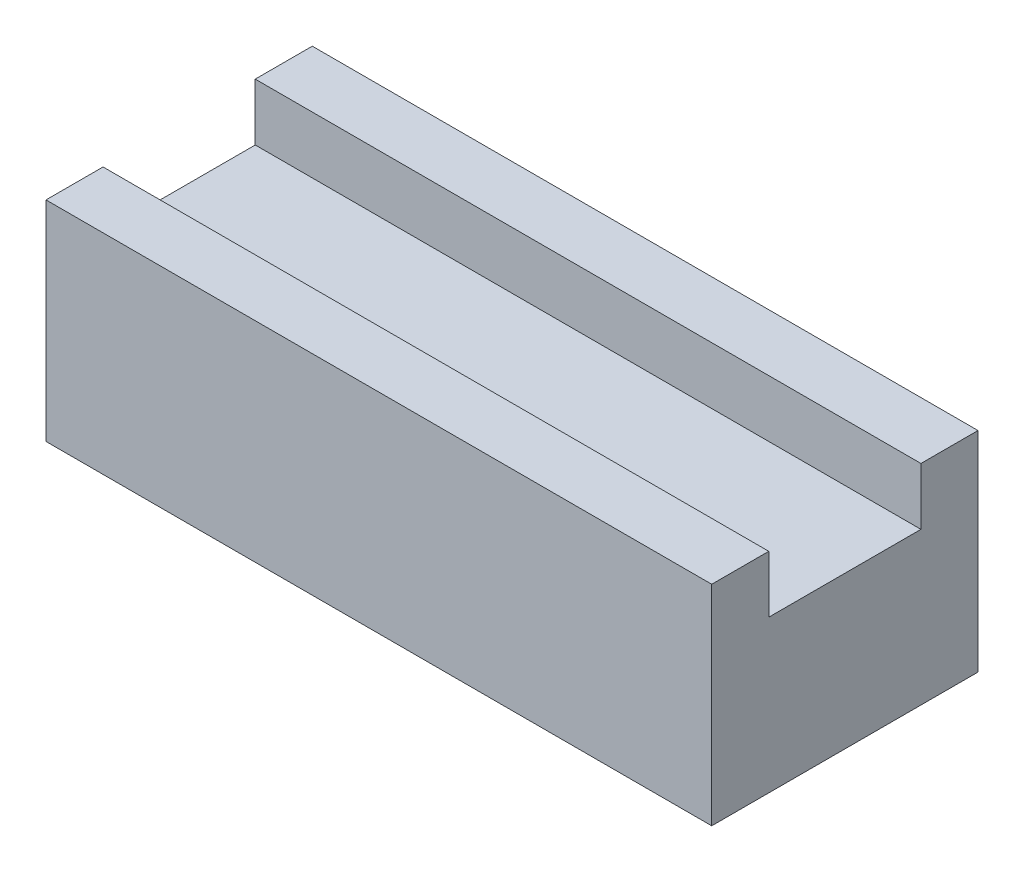
SolidWorks part; units mm, degrees
ref_plane "Front Plane" through (0, 0, 0) normal (0, 0, 1) x (1, 0, 0)
ref_plane "Top Plane" through (0, 0, 0) normal (0, 1, 0) x (1, 0, 0)
ref_plane "Right Plane" through (0, 0, 0) normal (1, 0, 0) x (0, 0, -1)
sketch "Sketch1" plane through (0, 0, 0) normal (1, 0, 0) x (0, 0, -1)
  line L0 (-7, 4) -> (-7, 7)
  line L1 (-7, -4) -> (7, -4)
  line L2 (-7, -4) -> (-7, 4)
  line L3 (-4, 4) -> (4, 4)
  line L4 (7, -4) -> (7, 4)
  line L5 (-7, -4) -> (7, 4) construction
  line L6 (-7, 4) -> (7, -4) construction
  line L7 (-7, 7) -> (-4, 7)
  line L8 (-4, 7) -> (-4, 4)
  line L9 (7, 4) -> (7, 7)
  line L10 (7, 7) -> (4, 7)
  line L11 (4, 7) -> (4, 4)
  point P0 (0, 0)
  point P12 (0, 4)
  point P13 (-4, 1.3048)
  point P14 (0, 0)
  point P15 (-7, 2.3631)
  dimension "D1" = 8
  dimension "D2" = 8
  dimension "D3" = 3
  dimension "D4" = 3
extrude "Boss-Extrude1" add sketch "Sketch1" against normal blind 35
